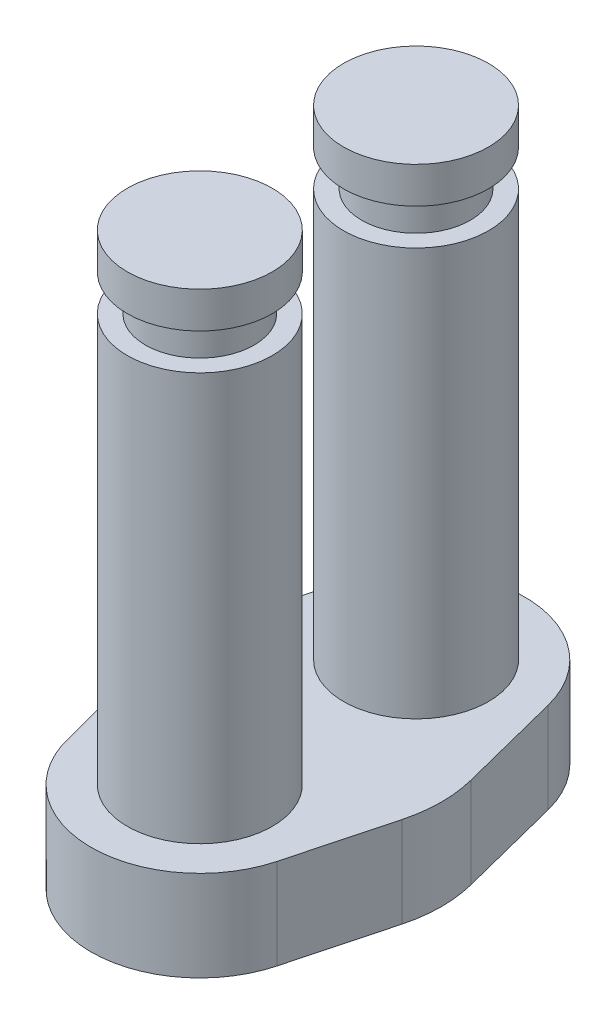
SolidWorks part; units mm, degrees
ref_plane "Front Plane" through (0, 0, 0) normal (0, 0, 1) x (1, 0, 0)
ref_plane "Top Plane" through (0, 0, 0) normal (0, 1, 0) x (1, 0, 0)
ref_plane "Right Plane" through (0, 0, 0) normal (1, 0, 0) x (0, 0, -1)
sketch "Sketch2" plane through (0, 0, 0) normal (0, 1, 0) x (1, 0, 0)
  line L0 (3.75, 7.5) -> (3.75, -7.5) construction
  line L1 (-3.4934, -1.9449) -> (-1.9217, -7.7985)
  line L2 (10.9985, -1.9261) -> (9.5488, -7.3818)
  line L3 (11.0189, 1.8474) -> (9.5651, 7.5676)
  line L4 (-2.0651, 7.5676) -> (-3.5189, 1.8474)
  circle A0 centre (7.5, 0) radius 2.5 construction
  circle A1 centre (0, 0) radius 2.5 construction
  circle A2 centre (3.75, 0) radius 7.5
  circle A3 centre (3.75, 6.0897) radius 4 construction
  circle A4 centre (3.75, -5.841) radius 4 construction
  circle A5 centre (3.75, 6.0897) radius 6
  circle A6 centre (3.75, -5.841) radius 6
  dimension "D1" = 7.5
  dimension "D2" = 5
  dimension "D4" = 15
  dimension "D5" = 12
  dimension "D6" = 12
  dimension "D7" = 8
  dimension "D8" = 8
  dimension "D3" = 3.75
extrude "Boss-Extrude2" add sketch "Sketch2" along normal blind 5 contours A2 A6 A0 A5 A1 | A6 A2 L1 | A6 A2 A5 A0 | A6 L2 A2 | A6 A1 A5 A2 | A6 A2 L1 | A6 A0 A5 | A5 A6 | A6 A5 A1 | A6 A5 A0 A2 A1 | A2 A5 | A5 A2 L3 | A5 L4 A2
sketch "Sketch3" plane through (0, 5, 0) normal (0, 1, 0) x (1, 0, 0)
  line L0 (3.75, -11.841) -> (3.75, 12.0897) construction
  line L1 (-3.7498, -0.0504) -> (11.2499, -0.0406) construction
  circle A0 centre (3.75, -5.841) radius 4
  circle A1 centre (3.75, 6.0897) radius 4
  arc A2 (-1.9217, -7.7985) -> (9.5488, -7.3818) centre (3.75, -5.841) ccw construction
  arc A3 (9.5651, 7.5676) -> (-2.0651, 7.5676) centre (3.75, 6.0897) ccw construction
  arc A4 (-3.5189, 1.8474) -> (-3.4934, -1.9449) centre (3.75, 0) ccw construction
  arc A5 (10.9985, -1.9261) -> (11.0189, 1.8474) centre (3.75, 0) ccw construction
  dimension "D1" = 8
extrude "Boss-Extrude3" add sketch "Sketch3" along normal blind 22.5
sketch "Sketch4" plane through (0, 27.5, 0) normal (0, 1, 0) x (1, 0, 0)
  circle A0 centre (3.75, -5.841) radius 3
  circle A1 centre (3.75, 6.0897) radius 3
  circle A2 centre (3.75, -5.841) radius 4 construction
  circle A3 centre (3.75, 6.0897) radius 4 construction
  dimension "D1" = 6
  dimension "D2" = 6
extrude "Boss-Extrude4" add sketch "Sketch4" along normal blind 2
sketch "Sketch5" plane through (0, 29.5, 0) normal (0, 1, 0) x (1, 0, 0)
  circle A0 centre (3.75, -5.841) radius 4
  circle A1 centre (3.75, 6.0897) radius 4
  dimension "D1" = 8
  dimension "D2" = 8
extrude "Boss-Extrude5" add sketch "Sketch5" along normal blind 2
hole_wizard "#6 Clearance Hole1" positions "Sketch6" profile "Sketch7" hole size "#6" standard "ANSI Inch"
sketch "Sketch6" plane through (0, 5, 0) normal (0, 1, 0) x (1, 0, 0)
  point P7 (3.75, 6.0897)
  point P10 (3.75, -5.841)
sketch "Sketch7" plane through (3.75, 5, -6.0897) normal (1, 0, 0) x (0, 0, 1)
  line L0 (0, 0) -> (0, 5)
  line L1 (0, 5) -> (1.8986, 5)
  line L2 (1.8986, 5) -> (1.8986, 0)
  line L5 (1.8986, 0) -> (0, 0)
  line L11 (0, -6.35) -> (0, 107.95) construction
  dimension "Thru Hole Dia." = 3.7973
  dimension "Thru Hole Depth" = 5
